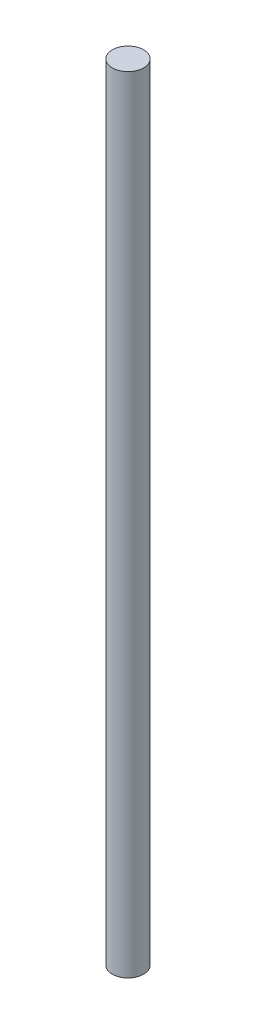
SolidWorks part; units mm, degrees
ref_plane "前视基准面" through (0, 0, 0) normal (0, 0, 1) x (1, 0, 0)
ref_plane "上视基准面" through (0, 0, 0) normal (0, 1, 0) x (1, 0, 0)
ref_plane "右视基准面" through (0, 0, 0) normal (1, 0, 0) x (0, 0, -1)
sketch "草图1" plane through (0, 0, 0) normal (0, 1, 0) x (1, 0, 0)
  circle A0 centre (0, 0) radius 2
  dimension "D1" = 4
extrude "凸台-拉伸1" add sketch "草图1" along normal blind 100
